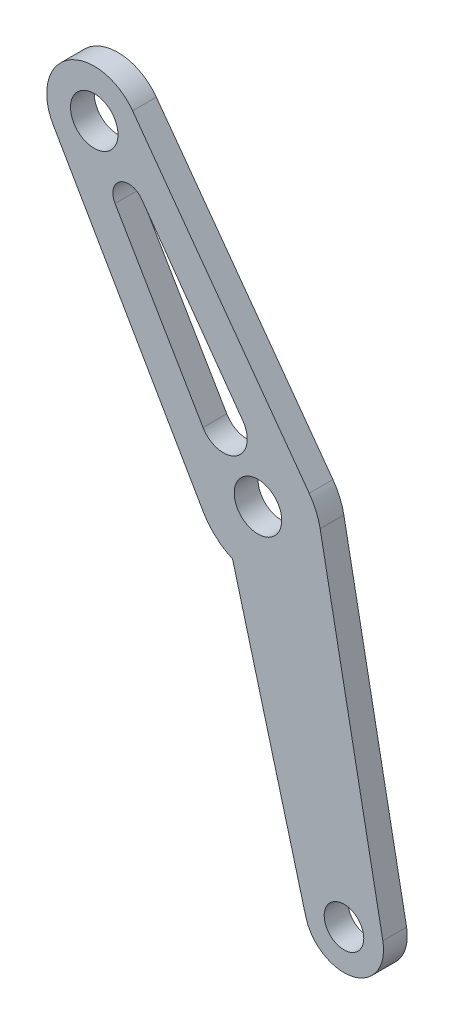
SolidWorks part; units mm, degrees
ref_plane "前视基准面" through (0, 0, 0) normal (0, 0, 1) x (1, 0, 0)
ref_plane "上视基准面" through (0, 0, 0) normal (0, 1, 0) x (1, 0, 0)
ref_plane "右视基准面" through (0, 0, 0) normal (1, 0, 0) x (0, 0, -1)
sketch "草图2" plane through (0, 0, 0) normal (0, 0, 1) x (1, 0, 0)
  line L0 (-1.1837, -107.9266) -> (-1.1837, 28.99) construction
  line L1 (-83.2547, -41.0466) -> (83.2547, -41.0466) construction
  line L3 (-12.0541, -0.4777) -> (-82.4527, 107.9266) construction
  line L4 (-37.9474, 28.3933) -> (-18.9835, -4.4757)
  line L5 (-27.8973, 34.9199) -> (-5.5834, 4.2265)
  line L6 (-15.2674, -7.804) -> (-6.0133, -42.3407)
  line L7 (3.726, -40.1008) -> (-4.1986, 1.0356)
  line L8 (-30.1184, 23.6705) -> (-18.9989, 4.7138)
  line L9 (-26.7672, 25.8468) -> (-13.9721, 7.9782)
  circle A0 centre (-1.1837, -41.0466) radius 2.5
  circle A1 centre (-12.0541, -0.4777) radius 3
  circle A2 centre (-32.7504, 31.3918) radius 3
  arc A3 (-27.8973, 34.9199) -> (-37.9474, 28.3933) centre (-32.7504, 31.3918) ccw
  arc A4 (-6.0133, -42.3407) -> (3.726, -40.1008) centre (-1.1837, -41.0466) ccw
  arc A5 (-18.9835, -4.4757) -> (-15.2674, -7.804) centre (-12.0541, -0.4777) ccw
  arc A6 (-4.1986, 1.0356) -> (-5.5834, 4.2265) centre (-12.0541, -0.4777) ccw
  arc A7 (-26.7672, 25.8468) -> (-30.1184, 23.6705) centre (-28.3933, 24.6824) ccw
  arc A8 (-18.9989, 4.7138) -> (-13.9721, 7.9782) centre (-16.4112, 6.2316) ccw
  point P27 (0, 0)
  point P28 (0, 0)
  dimension "D5" = 5
  dimension "D6" = 6
  dimension "D7" = 6
  dimension "D8" = 12
  dimension "D9" = 16
  dimension "D11" = 5
  dimension "D14" = 4
  dimension "D15" = 6
  dimension "D2" = 42
  dimension "D3" = 33
  dimension "D4" = 38
  dimension "D12" = 8
  dimension "D13" = 8
extrude "凸台-拉伸1" add sketch "草图2" along normal blind 3
